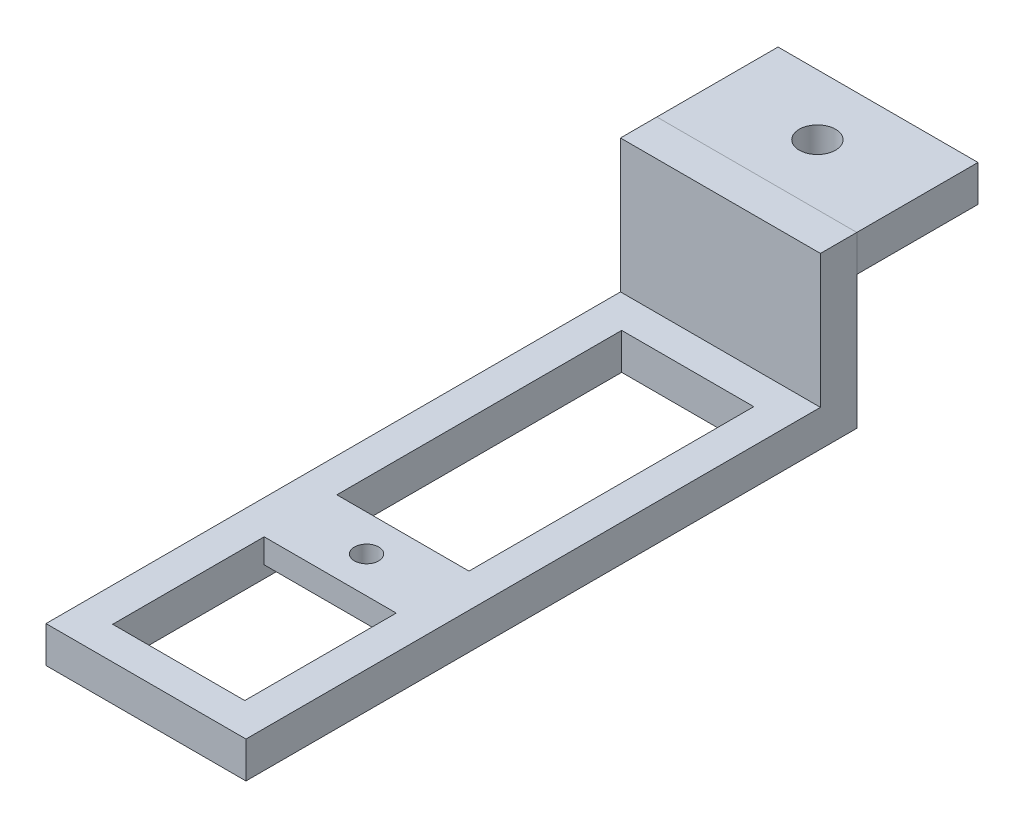
SolidWorks part; units mm, degrees
ref_plane "Front Plane" through (0, 0, 0) normal (0, 0, 1) x (1, 0, 0)
ref_plane "Top Plane" through (0, 0, 0) normal (0, 1, 0) x (1, 0, 0)
ref_plane "Right Plane" through (0, 0, 0) normal (1, 0, 0) x (0, 0, -1)
sketch "Sketch1" plane through (0, 0, 0) normal (0, 0, 1) x (1, 0, 0)
  line L1 (98.6394, -11.1578) -> (-71.3606, -11.1578)
  line L2 (98.6394, -11.1578) -> (98.6394, -8.1578)
  line L3 (98.6394, -8.1578) -> (-71.3606, -8.1578)
  line L4 (-71.3606, -11.1578) -> (-71.3606, -8.1578)
  line L5 (98.6394, -11.1578) -> (-71.3606, -8.1578) construction
  line L6 (98.6394, -8.1578) -> (-71.3606, -11.1578) construction
  point P0 (13.6394, -9.6578)
extrude "Boss-Extrude1" add sketch "Sketch1" along normal blind 10
sketch "Sketch2" plane through (0, -8.1578, 0) normal (0, 1, 0) x (1, 0, 0)
  line L0 (98.6394, -10) -> (-71.3606, -10) construction
  line L1 (-53.3606, -7) -> (-8.0606, -7)
  line L2 (-53.3606, -7) -> (-53.3606, -10)
  line L3 (-53.3606, -10) -> (-8.0606, -10)
  line L4 (-8.0606, -7) -> (-8.0606, -10)
  line L5 (-53.3606, -7) -> (-8.0606, -10) construction
  line L6 (-53.3606, -10) -> (-8.0606, -7) construction
  line L7 (-71.3606, -10) -> (-71.3606, 0) construction
  point P0 (-30.7106, -8.5)
  dimension "D1" = 0
  dimension "D2" = 18
sketch "Sketch4" plane through (0, -8.1578, 0) normal (0, 1, 0) x (1, 0, 0)
  line L0 (-71.3606, -10) -> (-71.3606, 0) construction
  line L1 (98.6394, -10) -> (98.6394, 0) construction
  circle A0 centre (-63.3606, -4.9385) radius 1.2
  circle A1 centre (90.6394, -5.2832) radius 1.2
  dimension "D1" = 8
  dimension "D2" = 8
extrude "Cut-Extrude1" cut sketch "Sketch4" against normal blind 21
extrude "Boss-Extrude6" add sketch "Sketch2" along normal blind 20.3
sketch "Sketch5" plane through (0, 0, 7) normal (0, 0, -1) x (-1, 0, 0)
  line L0 (8.0606, 12.1422) -> (8.0606, -8.1578) construction
  line L1 (53.3606, 12.1422) -> (53.3606, -8.1578) construction
  line L2 (8.0606, 12.1422) -> (53.3606, 12.1422) construction
  line L3 (27.5106, -5.4578) -> (33.9106, -5.4578) construction
  line L4 (27.5106, -3.5578) -> (33.9106, -3.5578)
  line L5 (27.5106, -7.3578) -> (33.9106, -7.3578)
  circle A0 centre (17.4606, 1.9422) radius 8.5
  circle A1 centre (43.9606, 1.9422) radius 8.5
  arc A2 (27.5106, -3.5578) -> (27.5106, -7.3578) centre (27.5106, -5.4578) ccw
  arc A3 (33.9106, -7.3578) -> (33.9106, -3.5578) centre (33.9106, -5.4578) ccw
  point P12 (30.7106, -5.4578)
  dimension "D1" = 26.5
  dimension "D6" = 1.9
  dimension "D2" = 9.4
  dimension "D3" = 9.4
  dimension "D4" = 10.2
  dimension "D5" = 10.2
  dimension "D7" = 6.4
  dimension "D8" = 15.7
  dimension "D9" = 19.45
  dimension "D10" = 19.45
extrude "Cut-Extrude2" cut sketch "Sketch5" against normal blind 20.3
sketch "Sketch6" plane through (0, -8.1578, 0) normal (0, 1, 0) x (1, 0, 0)
  line L0 (98.6394, -10) -> (-8.0606, -10) construction
  line L1 (35.3394, -7) -> (80.6394, -7)
  line L2 (35.3394, -7) -> (35.3394, -10)
  line L3 (35.3394, -10) -> (80.6394, -10)
  line L4 (80.6394, -7) -> (80.6394, -10)
  line L5 (35.3394, -7) -> (80.6394, -10) construction
  line L6 (35.3394, -10) -> (80.6394, -7) construction
  line L7 (98.6394, -10) -> (98.6394, 0) construction
  point P0 (57.9894, -8.5)
  point P9 (80.6394, -8.5)
  dimension "D1" = 0
  dimension "D2" = 18
extrude "Boss-Extrude7" add sketch "Sketch6" along normal blind 20.3
sketch "Sketch7" plane through (0, 0, 10) normal (0, 0, 1) x (1, 0, 0)
  line L0 (35.3394, 12.1422) -> (35.3394, -8.1578) construction
  line L1 (35.3394, 12.1422) -> (80.6394, 12.1422) construction
  line L3 (-33.9106, -7.3578) -> (-27.5106, -7.3578) construction
  line L4 (-71.3606, -11.1578) -> (98.6394, -11.1578) construction
  line L5 (-53.3606, 12.1422) -> (-53.3606, -8.1578) construction
  line L6 (54.8394, -5.4578) -> (61.2394, -5.4578) construction
  line L7 (54.8394, -3.5578) -> (61.2394, -3.5578)
  line L8 (54.8394, -7.3578) -> (61.2394, -7.3578)
  circle A0 centre (44.7394, 1.9422) radius 8.5
  circle A1 centre (71.2394, 1.9422) radius 8.5
  circle A2 centre (-43.9606, 1.9422) radius 8.5 construction
  circle A3 centre (-17.4606, 1.9422) radius 8.5 construction
  arc A5 (-33.9106, -3.5578) -> (-33.9106, -7.3578) centre (-33.9106, -5.4578) ccw construction
  arc A6 (54.8394, -3.5578) -> (54.8394, -7.3578) centre (54.8394, -5.4578) ccw
  arc A7 (61.2394, -7.3578) -> (61.2394, -3.5578) centre (61.2394, -5.4578) ccw
  point P23 (58.0394, -5.4578)
  dimension "D1" = 26.5
  dimension "D6" = 3.8
  dimension "D7" = 19.45
  dimension "D9" = 19.5
  dimension "D10" = 1.9
  dimension "D2" = 26.5
  dimension "D3" = 9.4
  dimension "D4" = 10.2
  dimension "D5" = 10.2
  dimension "D8" = 3.8
extrude "Cut-Extrude3" cut sketch "Sketch7" against normal through all
sketch "Sketch11" plane through (98.6394, 0, 0) normal (1, 0, 0) x (0, 0, -1)
  line L0 (-10, -11.1578) -> (-10, -8.1578) construction
  line L1 (-10, -22.1578) -> (-13, -22.1578)
  line L2 (-10, -22.1578) -> (-10, -8.1578)
  line L3 (-10, -8.1578) -> (-13, -8.1578)
  line L4 (-13, -22.1578) -> (-13, -8.1578)
  line L5 (-10, -22.1578) -> (-13, -8.1578) construction
  line L6 (-10, -8.1578) -> (-13, -22.1578) construction
  line L7 (-10, -8.1578) -> (0, -8.1578) construction
  point P0 (-11.5, -15.1578)
  dimension "D1" = 0
  dimension "D2" = 0
  dimension "D3" = 3
  dimension "D4" = 14
extrude "Boss-Extrude10" add sketch "Sketch11" along normal blind 16.5 separate body
move or copy body "Body-Move/Copy1" bodies to move or copy 125 copy no translate (-106.6404, 0, 0) parameters "D1"=106.6404, "D2"=0, "D3"=0
sketch "Sketch12" plane through (0, 0, 13) normal (0, 0, 1) x (1, 0, 0)
  line L1 (-8.001, -19.1578) -> (8.499, -19.1578)
  line L2 (-8.001, -19.1578) -> (-8.001, -22.1578)
  line L3 (-8.001, -22.1578) -> (8.499, -22.1578)
  line L4 (8.499, -19.1578) -> (8.499, -22.1578)
  line L5 (-8.001, -19.1578) -> (8.499, -22.1578) construction
  line L6 (-8.001, -22.1578) -> (8.499, -19.1578) construction
  point P0 (0.249, -20.6578)
  point P9 (0.7412, -20.8118)
extrude "Boss-Extrude11" add sketch "Sketch12" along normal blind 47.4
sketch "Sketch13" plane through (0, -19.1578, 0) normal (0, 1, 0) x (1, 0, 0)
  line L0 (-8.001, -60.4) -> (-8.001, -13) construction
  line L1 (5.699, -57.7) -> (-5.201, -57.7)
  line L2 (5.699, -57.7) -> (5.699, -15.7)
  line L3 (5.699, -15.7) -> (-5.201, -15.7)
  line L4 (-5.201, -57.7) -> (-5.201, -15.7)
  line L5 (5.699, -57.7) -> (-5.201, -15.7) construction
  line L6 (5.699, -15.7) -> (-5.201, -57.7) construction
  line L7 (8.499, -60.4) -> (-8.001, -60.4) construction
  line L8 (8.499, -60.4) -> (8.499, -13) construction
  point P0 (0.249, -36.7)
  dimension "D1" = 2.8
  dimension "D2" = 2.7
  dimension "D3" = 2.8
extrude "Cut-Extrude5" cut sketch "Sketch13" against normal through all
move or copy body "Body-Move/Copy3" bodies to move or copy 129 copy yes number of copies 1 translate (26.846, 0, 0) parameters "D1"=26.846, "D2"=0, "D3"=0
sketch "Sketch14" plane through (0, -19.1578, 0) normal (0, 1, 0) x (1, 0, 0)
  line L1 (-12.3889, -68.6783) -> (10.6111, -68.6783)
  line L2 (-12.3889, -68.6783) -> (-12.3889, -71.6783)
  line L3 (-12.3889, -71.6783) -> (10.6111, -71.6783)
  line L4 (10.6111, -68.6783) -> (10.6111, -71.6783)
  line L5 (-12.3889, -68.6783) -> (10.6111, -71.6783) construction
  line L6 (-12.3889, -71.6783) -> (10.6111, -68.6783) construction
  point P0 (-0.8889, -70.1783)
extrude "Boss-Extrude12" add sketch "Sketch14" against normal blind 9.5 separate body
sketch "Sketch15" plane through (0, 0, 71.6783) normal (0, 0, 1) x (1, 0, 0)
  line L0 (-12.3889, -19.1578) -> (10.6111, -19.1578) construction
  line L1 (7.6111, -25.6578) -> (-9.3889, -25.6578)
  line L2 (7.6111, -25.6578) -> (7.6111, -22.1578)
  line L3 (7.6111, -22.1578) -> (-9.3889, -22.1578)
  line L4 (-9.3889, -25.6578) -> (-9.3889, -22.1578)
  line L5 (7.6111, -25.6578) -> (-9.3889, -22.1578) construction
  line L6 (7.6111, -22.1578) -> (-9.3889, -25.6578) construction
  line L7 (-12.3889, -28.6578) -> (-12.3889, -19.1578) construction
  point P0 (-0.8889, -23.9078)
  dimension "D1" = 3
  dimension "D2" = 3
extrude "Cut-Extrude6" cut sketch "Sketch15" against normal blind 9.5
move or copy body "Body-Move/Copy4" bodies to move or copy 132 copy yes number of copies 1 translate (29.0983, 0, 0) parameters "D1"=29.0983, "D2"=0, "D3"=0
sketch "Sketch16" plane through (0, -8.1578, 0) normal (0, 1, 0) x (1, 0, 0)
  line L0 (-71.3606, -10) -> (-71.3606, 0) construction
  line L1 (-8.001, -15.1628) -> (-71.3606, -15.1628)
  line L2 (-8.001, -15.1628) -> (-8.001, 5.063)
  line L3 (-8.001, 5.063) -> (-71.3606, 5.063)
  line L4 (-71.3606, -15.1628) -> (-71.3606, 5.063)
  line L5 (-8.001, -15.1628) -> (-71.3606, 5.063) construction
  line L6 (-8.001, 5.063) -> (-71.3606, -15.1628) construction
  line L7 (98.6394, -15.3286) -> (35.3394, -15.3286)
  line L8 (98.6394, -15.3286) -> (98.6394, 8.5445)
  line L9 (98.6394, 8.5445) -> (35.3394, 8.5445)
  line L10 (35.3394, -15.3286) -> (35.3394, 8.5445)
  line L11 (98.6394, -15.3286) -> (35.3394, 8.5445) construction
  line L12 (98.6394, 8.5445) -> (35.3394, -15.3286) construction
  line L13 (-8.001, -10) -> (-8.001, -13) construction
  line L14 (98.6394, -10) -> (98.6394, 0) construction
  line L15 (35.3394, -7) -> (35.3394, -10) construction
  point P0 (-39.6808, -5.0499)
  point P5 (66.9894, -3.3921)
  dimension "D1" = 0
  dimension "D2" = 0
  dimension "D3" = 0
  dimension "D4" = 0
extrude "Cut-Extrude7" cut sketch "Sketch16" against normal through all both and the other way through all
sketch "Sketch17" plane through (0, -8.1578, 0) normal (0, 1, 0) x (1, 0, 0)
  line L0 (35.3394, -10) -> (-8.001, -10) construction
  line L1 (8.499, 9.9659) -> (18.845, 9.9659)
  line L2 (8.499, 9.9659) -> (8.499, -10)
  line L3 (8.499, -10) -> (18.845, -10)
  line L4 (18.845, 9.9659) -> (18.845, -10)
  line L5 (8.499, 9.9659) -> (18.845, -10) construction
  line L6 (8.499, -10) -> (18.845, 9.9659) construction
  line L7 (18.845, -10) -> (18.845, -13) construction
  line L8 (8.499, -10) -> (8.499, -13) construction
  point P0 (13.672, -0.017)
  dimension "D1" = 0
  dimension "D2" = 0
  dimension "D3" = 0
extrude "Cut-Extrude9" cut sketch "Sketch17" against normal through all both and the other way through all
sketch "Sketch18" plane through (0, -8.1578, 0) normal (0, 1, 0) x (1, 0, 0)
  line L0 (-8.001, 0) -> (-8.001, -10) construction
  line L1 (8.499, -10) -> (-8.001, -10) construction
  line L2 (18.845, 0) -> (18.845, -10) construction
  line L3 (35.3394, -10) -> (18.845, -10) construction
  circle A0 centre (0.249, -5) radius 1.5
  circle A1 centre (27.095, -5) radius 1.5
  dimension "D1" = 8.25
  dimension "D2" = 5
  dimension "D3" = 8.25
  dimension "D4" = 5
extrude "Cut-Extrude10" cut sketch "Sketch18" against normal blind 10
sketch "Sketch22" plane through (0, -8.1578, 0) normal (0, 1, 0) x (1, 0, 0)
  line L1 (46.0008, -74.4413) -> (15.3403, -74.4413)
  line L2 (46.0008, -74.4413) -> (46.0008, 11.03)
  line L3 (46.0008, 11.03) -> (15.3403, 11.03)
  line L4 (15.3403, -74.4413) -> (15.3403, 11.03)
  line L5 (46.0008, -74.4413) -> (15.3403, 11.03) construction
  line L6 (46.0008, 11.03) -> (15.3403, -74.4413) construction
  point P0 (30.6705, -31.7056)
extrude "Cut-Extrude14" cut sketch "Sketch22" against normal through all
sketch "Sketch23" plane through (0, -19.1578, 0) normal (0, 1, 0) x (1, 0, 0)
  line L1 (-15.6494, -66.8903) -> (14.6226, -66.8903)
  line L2 (-15.6494, -66.8903) -> (-15.6494, -74.1737)
  line L3 (-15.6494, -74.1737) -> (14.6226, -74.1737)
  line L4 (14.6226, -66.8903) -> (14.6226, -74.1737)
  line L5 (-15.6494, -66.8903) -> (14.6226, -74.1737) construction
  line L6 (-15.6494, -74.1737) -> (14.6226, -66.8903) construction
  point P0 (-0.5134, -70.532)
extrude "Cut-Extrude15" cut sketch "Sketch23" against normal through all
sketch "Sketch24" plane through (0, -19.1578, 0) normal (0, 1, 0) x (1, 0, 0)
  line L1 (5.699, -45.2) -> (-5.201, -45.2)
  line L2 (5.699, -45.2) -> (5.699, -39.2)
  line L3 (5.699, -39.2) -> (-5.201, -39.2)
  line L4 (-5.201, -45.2) -> (-5.201, -39.2)
  line L5 (5.699, -45.2) -> (-5.201, -39.2) construction
  line L6 (5.699, -39.2) -> (-5.201, -45.2) construction
  line L7 (5.699, -57.7) -> (5.699, -15.7) construction
  line L8 (-5.201, -57.7) -> (5.699, -57.7) construction
  line L9 (-5.201, -15.7) -> (-5.201, -57.7) construction
  circle A0 centre (0.249, -42.2) radius 1
  point P0 (0.249, -42.2)
  dimension "D4" = 3
  dimension "D5" = 5.45
  dimension "D1" = 0
  dimension "D2" = 0
  dimension "D3" = 12.5
extrude "Boss-Extrude13" add sketch "Sketch24" against normal blind 2
